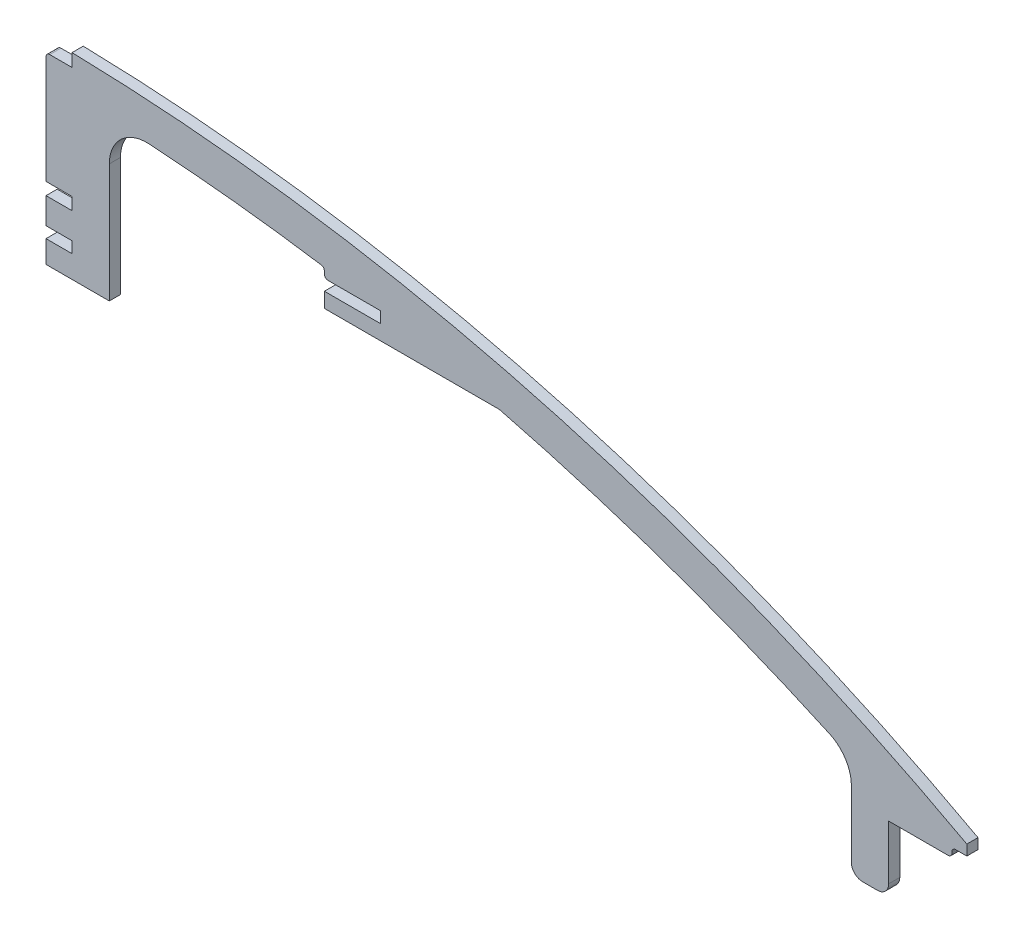
SolidWorks part; units mm, degrees
ref_plane "Front Plane" through (0, 0, 0) normal (0, 0, 1) x (1, 0, 0)
ref_plane "Top Plane" through (0, 0, 0) normal (0, 1, 0) x (1, 0, 0)
ref_plane "Right Plane" through (0, 0, 0) normal (1, 0, 0) x (0, 0, -1)
sketch "Sketch1" plane through (0, 0, 0) normal (0, 0, 1) x (1, 0, 0)
  line L0 (-45, 0) -> (45, 0) construction
  line L1 (300, -65.3534) -> (300, -85.3534)
  line L2 (-45, -150.7069) -> (45, -150.7069) construction
  line L3 (-45, 0) -> (-45, -150.7069) construction
  line L4 (45, 0) -> (45, -150.7069) construction
  line L5 (0, 0) -> (0, -150.7069)
  line L6 (45, 0) -> (0, 0)
  line L7 (0, -150.7069) -> (45, -150.7069)
  line L8 (276.5, -53.2137) -> (276.5, -97.4932)
  line L9 (300, -69.7034) -> (276.5, -69.7034)
  arc A0 (45, 0) -> (300, -65.3534) centre (45, -530.1639) cw
  arc A1 (-28.1177, 0) -> (35.3823, 0) centre (3.6323, -0.0236) cw construction
  arc A2 (45, -150.7069) -> (300, -85.3534) centre (45, 379.457) ccw
  point P4 (0, 0)
  dimension "D2" = 300
  dimension "D3" = 31.75
  dimension "D5" = 150.7069
  dimension "D1" = 90
  dimension "D4" = 20
  dimension "D6" = 276.5
  dimension "D7" = 4.35
sketch "Sketch2" plane through (0, 0, 0) normal (0, 0, 1) x (1, 0, 0)
  line L0 (299.5, -67.3534) -> (294.5, -67.3534)
  line L4 (300, -65.3534) -> (300, -85.3534) construction
  line L5 (300, -65.3534) -> (300, -85.3534) construction
  line L6 (299.5, -65.6495) -> (299.5, -67.3534)
  line L12 (45, -0.5) -> (0.5, -0.5)
  line L13 (0.5, -0.5) -> (0.5, -150.2069)
  line L14 (0.5, -150.2069) -> (45, -150.2069)
  line L15 (299.5, -85.0574) -> (299.5, -65.6495)
  line L20 (55, -13.5) -> (25, -13.5) construction
  line L21 (55, -10.5962) -> (55, -13.5) construction
  line L22 (140, -19.2573) -> (140, -22.2573)
  line L23 (140, -19.2573) -> (126, -19.2573)
  line L24 (125, -18.2573) -> (125, -17.5517)
  line L26 (0, 0) -> (0, -150.7069) construction
  line L27 (45, -3.5) -> (25, -3.5) construction
  line L28 (45, -0.5) -> (45, -3.5) construction
  line L29 (293.5, -68.3534) -> (293.5, -68.7034)
  line L30 (300, -69.7034) -> (276.5, -69.7034) construction
  line L31 (292.5, -69.7034) -> (276.5, -69.7034)
  line L32 (276.5, -69.7034) -> (276.5, -84.3212)
  line L33 (276.5, -53.2137) -> (276.5, -97.4932) construction
  line L34 (273.5, -87.3212) -> (269.5, -87.3212)
  line L35 (266.5, -84.3212) -> (266.5, -66.456)
  line L36 (57.25, -0.6417) -> (57.25, -4.1022)
  line L37 (51.25, -4.1022) -> (57.25, -4.1022)
  line L38 (50.25, -5.1022) -> (50.25, -34.1022)
  line L40 (50.25, -34.1022) -> (57.25, -34.1022)
  line L41 (57.25, -34.1022) -> (57.25, -37.4022)
  line L42 (57.25, -37.4022) -> (50.25, -37.4022)
  line L43 (50.25, -37.4022) -> (50.25, -44.4022)
  line L44 (50.25, -44.4022) -> (57.25, -44.4022)
  line L45 (0, -1.1022) -> (70.25, -1.1022) construction
  line L46 (67.25, -38.8) -> (67.25, -21.5214)
  line L47 (57.25, -34.1022) -> (57.25, -37.4022)
  line L49 (140, -22.2573) -> (125, -22.2573)
  line L50 (125, -22.2573) -> (125, -26.2573)
  line L51 (125, -26.2573) -> (171.9988, -26.2573)
  line L52 (67.25, -38.8) -> (67.25, -53.4022)
  line L53 (67.25, -53.4022) -> (50.25, -53.4022)
  line L54 (50.25, -53.4022) -> (50.25, -47.4022)
  line L55 (50.25, -47.4022) -> (57.25, -47.4022)
  line L56 (57.25, -47.4022) -> (57.25, -44.4022)
  arc A0 (260.6498, -57.3577) -> (163.7816, -24.2573) centre (45, -530.1639) ccw
  arc A1 (294.6951, -74.4195) -> (55, -10.5962) centre (45, -530.1639) ccw construction
  arc A5 (124.1523, -16.5634) -> (77.8828, -11.5414) centre (45, -530.1639) ccw
  arc A6 (45, -150.2069) -> (299.5, -85.0574) centre (45, 379.457) ccw
  arc A7 (299.5, -65.6495) -> (45, -0.5) centre (45, -530.1639) ccw
  arc A9 (299.5, -65.6495) -> (57.25, -0.6417) centre (45, -530.1639) ccw
  arc A10 (125, -16.6947) -> (163.7816, -24.2573) centre (45, -530.1639) cw construction
  arc A12 (126, -19.2573) -> (125, -18.2573) centre (126, -18.2573) cw
  arc A13 (125, -17.5517) -> (124.1523, -16.5634) centre (124, -17.5517) ccw
  arc A16 (299.5, -65.6495) -> (45, -0.5) centre (45, -530.1639) ccw construction
  arc A18 (266.5, -66.456) -> (260.6498, -57.3577) centre (256.5, -66.456) ccw
  arc A19 (269.5, -87.3212) -> (266.5, -84.3212) centre (269.5, -84.3212) cw
  arc A20 (276.5, -84.3212) -> (273.5, -87.3212) centre (273.5, -84.3212) cw
  arc A21 (294.5, -67.3534) -> (293.5, -68.3534) centre (294.5, -68.3534) ccw
  arc A22 (293.5, -68.7034) -> (292.5, -69.7034) centre (292.5, -68.7034) cw
  arc A23 (67.25, -21.5214) -> (77.8828, -11.5414) centre (77.25, -21.5214) cw
  arc A29 (50.25, -5.1022) -> (51.25, -4.1022) centre (51.25, -5.1022) cw
  point P10 (0, 0)
  point P26 (300, -75.3534)
  point P33 (291.5, -67.3534)
  point P43 (140, -24.2573)
  point P48 (125, -19.2573)
  point P66 (266.5, -87.3212)
  point P69 (276.5, -87.3212)
  point P75 (293.5, -69.7034)
  point P80 (50.25, -44.4022)
  point P85 (50.25, -37.4022)
  point P88 (50.25, -34.1022)
  point P91 (50.25, -4.1022)
  dimension "D5" = 3.3
  dimension "D10" = 10
  dimension "D11" = 3
  dimension "D16" = 3
  dimension "D17" = 10
  dimension "D18" = 50.25
  dimension "D12" = 1
  dimension "D20" = 10
  dimension "D21" = 6
  dimension "D22" = 3
  dimension "D23" = 70.25
  dimension "D3" = 30
  dimension "D6" = 7
  dimension "D7" = 8
  dimension "D8" = 8
  dimension "D9" = 10
  dimension "D13" = 15
  dimension "D14" = 5
  dimension "D15" = 140
  dimension "D19" = 57.25
  dimension "D24" = 3
  dimension "D25" = 4
  dimension "D1" = 0.5
  dimension "D4" = 10
extrude "Boss-Extrude1" add sketch "Sketch2" along normal mid plane 3
sketch "Sketch4" plane through (0, 0, -1.5) normal (0, 0, 1) x (1, 0, 0)
  line L1 (297.5, -62.5957) -> (299.5, -62.5957)
  line L2 (297.5, -62.5957) -> (297.5, -69.6147)
  line L3 (297.5, -69.6147) -> (299.5, -69.6147)
  line L4 (299.5, -62.5957) -> (299.5, -69.6147)
  line L5 (299.5, -65.6495) -> (299.5, -67.3534) construction
  dimension "D1" = 2
extrude "Cut-Extrude2" cut sketch "Sketch4" along normal up to surface (3 mm away) up to face at (152.0274, -41.9242, 1.5)
